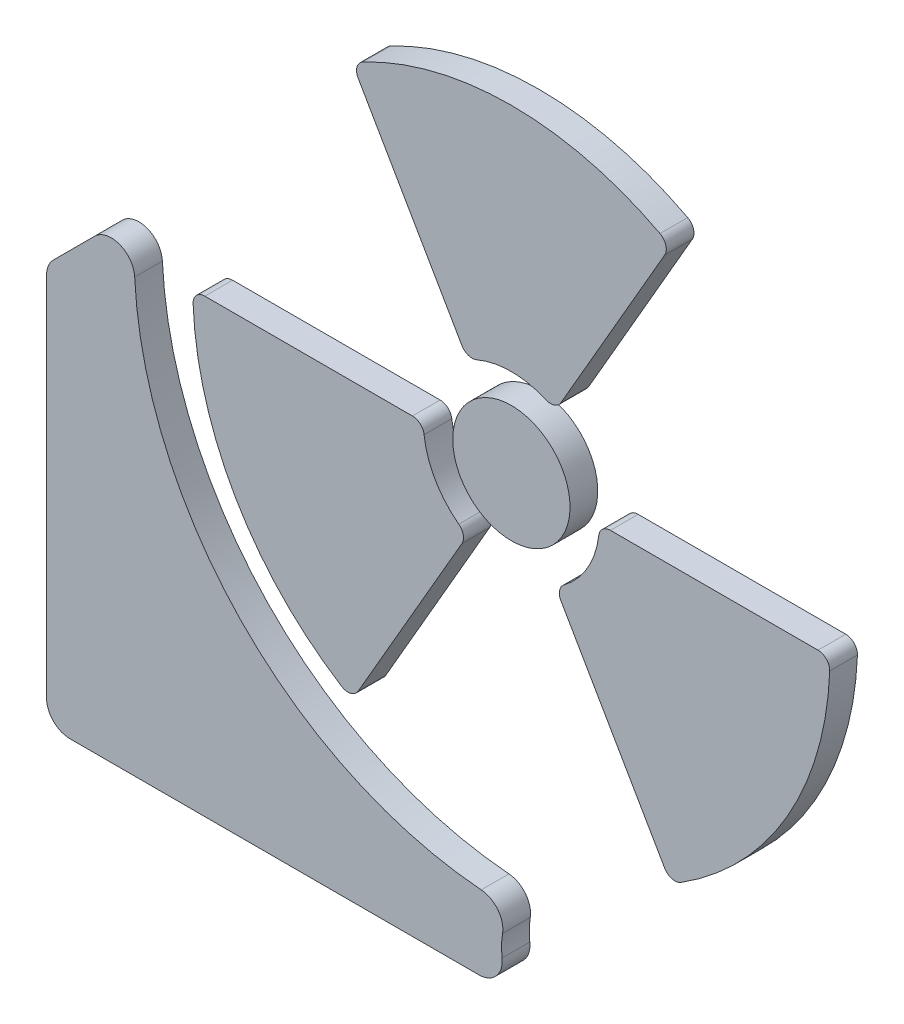
SolidWorks part; units mm, degrees
material "Custom Plastic"
ref_plane "Front Plane" through (0, 0, 0) normal (0, 0, 1) x (1, 0, 0)
ref_plane "Top Plane" through (0, 0, 0) normal (0, 1, 0) x (1, 0, 0)
ref_plane "Right Plane" through (0, 0, 0) normal (1, 0, 0) x (0, 0, -1)
sketch "Sketch1" plane through (0, 0, 0) normal (0, 0, 1) x (1, 0, 0)
  line L1 (50.8, -50.8) -> (-50.8, -50.8)
  line L2 (50.8, -50.8) -> (50.8, 50.8)
  line L3 (50.8, 50.8) -> (-50.8, 50.8)
  line L4 (-50.8, -50.8) -> (-50.8, 50.8)
  line L5 (50.8, -50.8) -> (-50.8, 50.8) construction
  line L6 (50.8, 50.8) -> (-50.8, -50.8) construction
  point P0 (0, 0)
  dimension "D1" = 101.6
  dimension "D2" = 101.6
extrude "Boss-Extrude1" add sketch "Sketch1" along normal blind 3
sketch "Sketch3" plane through (0, 0, 0) normal (0, 0, -1) x (-1, 0, 0)
  line L2 (-4.5929, 0.6691) -> (6.6485, -18.8016)
  line L3 (23.2499, 9.9529) -> (0.7671, 9.9529)
  line L4 (-4.5929, 0.6691) -> (6.6485, -18.8016)
  line L5 (23.2499, 9.9529) -> (0.7671, 9.9529)
  line L6 (-20.6729, 9.9529) -> (-43.1557, 9.9529)
  line L7 (-26.5543, -18.8016) -> (-15.3129, 0.6691)
  line L8 (-20.6729, 9.9529) -> (-43.1557, 9.9529)
  line L9 (-26.5543, -18.8016) -> (-15.3129, 0.6691)
  line L10 (-4.5929, 19.2367) -> (6.6485, 38.7074)
  line L11 (-26.5543, 38.7074) -> (-15.3129, 19.2367)
  line L12 (-4.5929, 19.2367) -> (6.6485, 38.7074)
  line L13 (-26.5543, 38.7074) -> (-15.3129, 19.2367)
  line L15 (-6.419, -38.862) -> (37.846, -38.862)
  line L16 (39.6421, 5.1491) -> (35.1777, 9.6134)
  line L17 (40.386, -36.322) -> (40.386, 3.353)
  line L18 (-6.419, -38.862) -> (37.846, -38.862)
  line L19 (39.6421, 5.1491) -> (35.1777, 9.6134)
  line L20 (40.386, -36.322) -> (40.386, 3.353)
  circle A1 centre (-9.9529, 9.9529) radius 6.35
  circle A2 centre (-9.9529, 9.9529) radius 6.35
  arc A6 (6.6485, -18.8016) -> (8.4249, -19.2414) centre (7.7484, -18.1666) ccw
  arc A7 (8.4249, -19.2414) -> (24.519, 8.6344) centre (-9.9529, 9.9529) ccw
  arc A8 (24.519, 8.6344) -> (23.2499, 9.9529) centre (23.2499, 8.6829) ccw
  arc A9 (0.7671, 9.9529) -> (-0.494, 8.8323) centre (0.7671, 8.6829) ccw
  arc A10 (-4.253, 2.3216) -> (-0.494, 8.8323) centre (-9.9529, 9.9529) ccw
  arc A11 (-4.253, 2.3216) -> (-4.5929, 0.6691) centre (-3.493, 1.3041) ccw
  arc A12 (6.6485, -18.8016) -> (8.4249, -19.2414) centre (7.7484, -18.1666) ccw
  arc A13 (8.4249, -19.2414) -> (24.519, 8.6344) centre (-9.9529, 9.9529) ccw
  arc A14 (24.519, 8.6344) -> (23.2499, 9.9529) centre (23.2499, 8.6829) ccw
  arc A15 (0.7671, 9.9529) -> (-0.494, 8.8323) centre (0.7671, 8.6829) ccw
  arc A16 (-4.253, 2.3216) -> (-0.494, 8.8323) centre (-9.9529, 9.9529) ccw
  arc A17 (-4.253, 2.3216) -> (-4.5929, 0.6691) centre (-3.493, 1.3041) ccw
  arc A18 (-44.4248, 8.6344) -> (-28.3307, -19.2414) centre (-9.9529, 9.9529) ccw
  arc A19 (-43.1557, 9.9529) -> (-44.4248, 8.6344) centre (-43.1557, 8.6829) ccw
  arc A20 (-19.4118, 8.8323) -> (-20.6729, 9.9529) centre (-20.6729, 8.6829) ccw
  arc A21 (-19.4118, 8.8323) -> (-15.6528, 2.3216) centre (-9.9529, 9.9529) ccw
  arc A22 (-15.3129, 0.6691) -> (-15.6528, 2.3216) centre (-16.4128, 1.3041) ccw
  arc A23 (-28.3307, -19.2414) -> (-26.5543, -18.8016) centre (-27.6542, -18.1666) ccw
  arc A24 (-44.4248, 8.6344) -> (-28.3307, -19.2414) centre (-9.9529, 9.9529) ccw
  arc A25 (-43.1557, 9.9529) -> (-44.4248, 8.6344) centre (-43.1557, 8.6829) ccw
  arc A26 (-19.4118, 8.8323) -> (-20.6729, 9.9529) centre (-20.6729, 8.6829) ccw
  arc A27 (-19.4118, 8.8323) -> (-15.6528, 2.3216) centre (-9.9529, 9.9529) ccw
  arc A28 (-15.3129, 0.6691) -> (-15.6528, 2.3216) centre (-16.4128, 1.3041) ccw
  arc A29 (-28.3307, -19.2414) -> (-26.5543, -18.8016) centre (-27.6542, -18.1666) ccw
  arc A30 (6.6485, 38.7074) -> (6.1412, 40.4657) centre (5.5487, 39.3424) ccw
  arc A31 (-6.1939, 18.7048) -> (-4.5929, 19.2367) centre (-5.6927, 19.8717) ccw
  arc A32 (-6.1939, 18.7048) -> (-13.7119, 18.7048) centre (-9.9529, 9.9529) ccw
  arc A33 (-15.3129, 19.2367) -> (-13.7119, 18.7048) centre (-14.2131, 19.8717) ccw
  arc A34 (-26.047, 40.4657) -> (-26.5543, 38.7074) centre (-25.4545, 39.3424) ccw
  arc A35 (6.1412, 40.4657) -> (-26.047, 40.4657) centre (-9.9529, 9.9529) ccw
  arc A36 (6.6485, 38.7074) -> (6.1412, 40.4657) centre (5.5487, 39.3424) ccw
  arc A37 (-6.1939, 18.7048) -> (-4.5929, 19.2367) centre (-5.6927, 19.8717) ccw
  arc A38 (-6.1939, 18.7048) -> (-13.7119, 18.7048) centre (-9.9529, 9.9529) ccw
  arc A39 (-15.3129, 19.2367) -> (-13.7119, 18.7048) centre (-14.2131, 19.8717) ccw
  arc A40 (-26.047, 40.4657) -> (-26.5543, 38.7074) centre (-25.4545, 39.3424) ccw
  arc A41 (6.1412, 40.4657) -> (-26.047, 40.4657) centre (-9.9529, 9.9529) ccw
  arc A45 (-8.9425, -36.0335) -> (-6.419, -38.862) centre (-6.419, -36.322) ccw
  arc A46 (-8.9425, -36.0335) -> (-8.9939, -33.6945) centre (-17.526, -35.052) ccw
  arc A47 (-6.6885, -30.7636) -> (-8.9939, -33.6945) centre (-6.4855, -33.2954) ccw
  arc A48 (-6.6885, -30.7636) -> (30.8447, 7.9424) centre (-9.9529, 9.9529) ccw
  arc A49 (35.1777, 9.6134) -> (30.8447, 7.9424) centre (33.3816, 7.8174) ccw
  arc A50 (40.386, 3.353) -> (39.6421, 5.1491) centre (37.846, 3.353) ccw
  arc A51 (37.846, -38.862) -> (40.386, -36.322) centre (37.846, -36.322) ccw
  arc A52 (-8.9425, -36.0335) -> (-6.419, -38.862) centre (-6.419, -36.322) ccw
  arc A53 (-8.9425, -36.0335) -> (-8.9939, -33.6945) centre (-17.526, -35.052) ccw
  arc A54 (-6.6885, -30.7636) -> (-8.9939, -33.6945) centre (-6.4855, -33.2954) ccw
  arc A55 (-6.6885, -30.7636) -> (30.8447, 7.9424) centre (-9.9529, 9.9529) ccw
  arc A56 (35.1777, 9.6134) -> (30.8447, 7.9424) centre (33.3816, 7.8174) ccw
  arc A57 (40.386, 3.353) -> (39.6421, 5.1491) centre (37.846, 3.353) ccw
  arc A58 (37.846, -38.862) -> (40.386, -36.322) centre (37.846, -36.322) ccw
  line M36 (50.8, -50.8) -> (50.8, 50.8)
  line M37 (50.8, 50.8) -> (-50.8, 50.8)
  line M38 (-50.8, 50.8) -> (-50.8, -50.8)
  line M39 (-50.8, -50.8) -> (50.8, -50.8)
  dimension "D1" = 0
  dimension "D2" = 0
  dimension "D3" = 0
  dimension "D4" = 0
  dimension "D5" = 0
extrude "Cut-Extrude1" cut sketch "Sketch3" against normal through all contours A58 L18 A52 A53 A54 A55 A56 L19 A57 L20 A41 A36 L12 A37 A38 A39 L13 A40 A29 A24 A25 L8 A26 A27 A28 L9 A17 A16 A15 L5 A14 A13 A12 L4 A2 M39 M36 M37 M38
